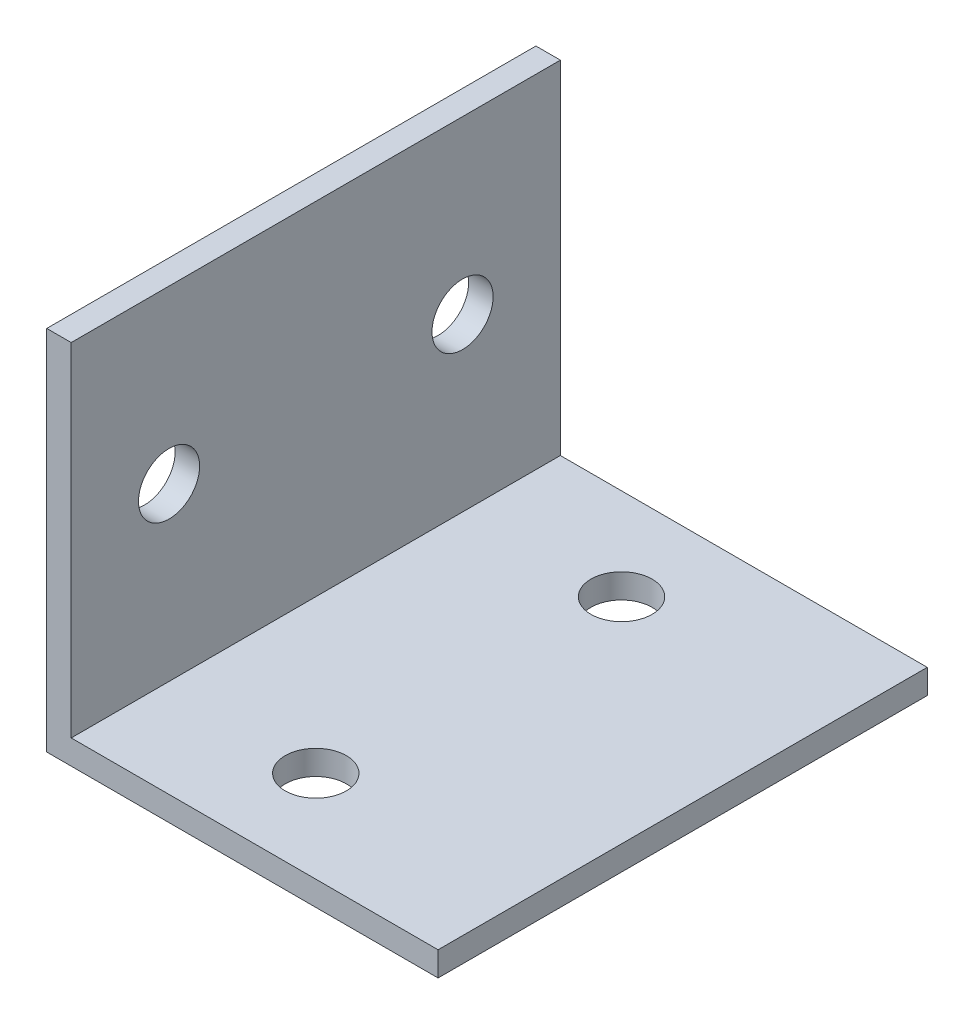
SolidWorks part; units mm, degrees
ref_plane "Front Plane" through (0, 0, 0) normal (0, 0, 1) x (1, 0, 0)
ref_plane "Top Plane" through (0, 0, 0) normal (0, 1, 0) x (1, 0, 0)
ref_plane "Right Plane" through (0, 0, 0) normal (1, 0, 0) x (0, 0, -1)
sketch "Sketch1" plane through (0, 0, 0) normal (0, 0, 1) x (1, 0, 0)
  line L0 (0, 0) -> (0, -30)
  line L1 (0, -30) -> (32, -30)
  line L2 (32, -30) -> (32, -28)
  line L3 (0, 0) -> (2, 0)
  line L4 (2, 0) -> (2, -28)
  line L5 (2, -28) -> (32, -28)
  dimension "D1" = 2
  dimension "D2" = 2
  dimension "D3" = 30
  dimension "D4" = 30
extrude "Boss-Extrude1" add sketch "Sketch1" along normal blind 40
hole_wizard "Tap Drill for M6x1.0 Tap1" positions "Sketch3" profile "Sketch2" hole size "M6x1.0" standard "ANSI Metric" end condition up to next
sketch "Sketch3" plane through (0, -28, 0) normal (0, 1, 0) x (1, 0, 0)
  line L1 (32, 0) -> (2, 0) construction
  line L3 (14.5, 0) -> (14.5, -7.5) construction
  line L9 (0, 0) -> (14.5, 0) construction
  line L11 (0, -40) -> (0, 0) construction
  point P0 (14.5, -7.5)
  point P2 (14.5, -32.5)
  dimension "D1" = 14.5
  dimension "D2" = 7.5
  dimension "D3" = 25
  dimension "D4" = 14.5
sketch "Sketch2" plane through (14.5, -28, 7.5) normal (1, 0, 0) x (0, 0, 1)
  line L0 (0, 0) -> (0, 2)
  line L1 (0, 2) -> (2.5, 2)
  line L2 (2.5, 2) -> (2.5, 0)
  line L5 (2.5, 0) -> (0, 0)
  line L11 (0, -6.35) -> (0, 107.95) construction
  dimension "Thru Hole Dia." = 5
  dimension "Thru Hole Depth" = 2
hole_wizard "Tap Drill for M6x1.0 Tap2" positions "Sketch6" profile "Sketch5" hole size "M6x1.0" standard "ANSI Metric" end condition up to next
sketch "Sketch6" plane through (2, 0, 0) normal (1, 0, 0) x (0, 0, -1)
  line L0 (-40, 0) -> (-40, -14) construction
  line L1 (-40, -28) -> (-40, 0) construction
  line L2 (-40, -14) -> (-32, -14) construction
  line L4 (0, -28) -> (0, 0) construction
  point P0 (-32, -14)
  point P2 (-8, -14)
  dimension "D1" = 14
  dimension "D2" = 8
  dimension "D3" = 8
sketch "Sketch5" plane through (2, -14, 32) normal (0, 1, 0) x (0, 0, -1)
  line L0 (0, 0) -> (0, 2)
  line L1 (0, 2) -> (2.5, 2)
  line L2 (2.5, 2) -> (2.5, 0)
  line L5 (2.5, 0) -> (0, 0)
  line L11 (0, -6.35) -> (0, 107.95) construction
  dimension "Thru Hole Dia." = 5
  dimension "Thru Hole Depth" = 2
